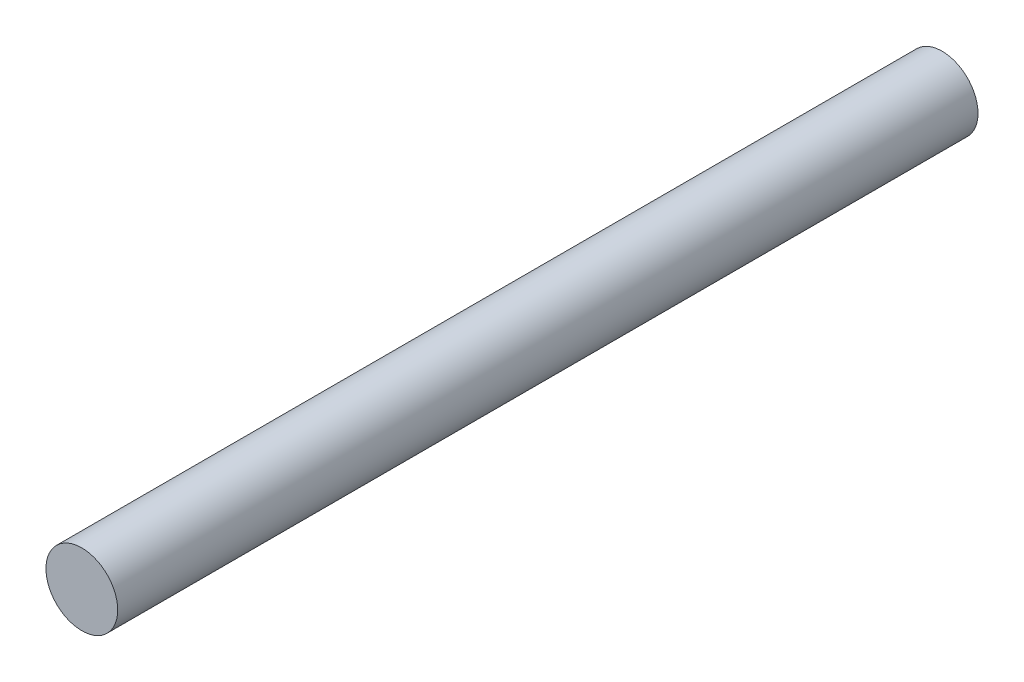
SolidWorks part; units mm, degrees
ref_plane "Plan de face" through (0, 0, 0) normal (0, 0, 1) x (1, 0, 0)
ref_plane "Plan de dessus" through (0, 0, 0) normal (0, 1, 0) x (1, 0, 0)
ref_plane "Plan de droite" through (0, 0, 0) normal (1, 0, 0) x (0, 0, -1)
sketch "Esquisse1" plane through (0, 0, 0) normal (0, 0, 1) x (1, 0, 0)
  circle A0 centre (0, 0) radius 1.585
  dimension "D1" = 3.17
extrude "Boss.-Extru.1" add sketch "Esquisse1" along normal blind 38
